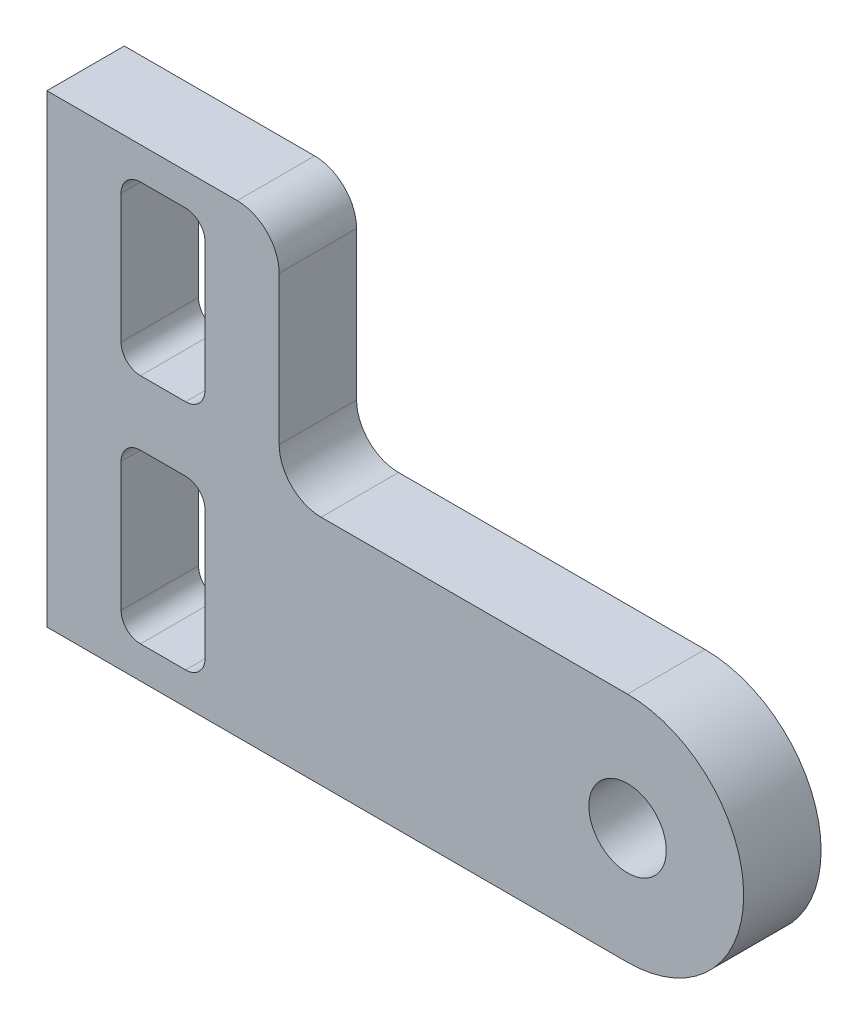
SolidWorks part; units mm, degrees
ref_plane "Alzado" through (0, 0, 0) normal (0, 0, 1) x (1, 0, 0)
ref_plane "Planta" through (0, 0, 0) normal (0, 1, 0) x (1, 0, 0)
ref_plane "Vista lateral" through (0, 0, 0) normal (1, 0, 0) x (0, 0, -1)
sketch "Model" plane through (0, 0, 0) normal (0, 0, 1) x (1, 0, 0)
  line L0 (182.2229, 265.8965) -> (183.9729, 265.8965)
  line L1 (184.7229, 266.6465) -> (184.7229, 271.6465)
  line L2 (183.9729, 272.3965) -> (182.2229, 272.3965)
  line L3 (181.4729, 271.6465) -> (181.4729, 266.6465)
  line L4 (185.9729, 282.6465) -> (178.5979, 282.6465)
  line L5 (182.2229, 274.896) -> (183.9729, 274.896)
  line L6 (184.7229, 275.646) -> (184.7229, 280.646)
  line L7 (183.9729, 281.396) -> (182.2229, 281.396)
  line L8 (181.4729, 280.646) -> (181.4729, 275.646)
  line L9 (178.5979, 282.6465) -> (178.5979, 264.6465)
  line L10 (187.5979, 281.0215) -> (187.5979, 275.2715)
  line L11 (189.2229, 273.6465) -> (201.0979, 273.6465)
  line L12 (201.0979, 264.6465) -> (178.5979, 264.6465)
  circle A0 centre (201.0979, 269.1465) radius 1.5
  arc A1 (181.4729, 266.6465) -> (182.2229, 265.8965) centre (182.2229, 266.6465) ccw
  arc A2 (183.9729, 265.8965) -> (184.7229, 266.6465) centre (183.9729, 266.6465) ccw
  arc A3 (184.7229, 271.6465) -> (183.9729, 272.3965) centre (183.9729, 271.6465) ccw
  arc A4 (182.2229, 272.3965) -> (181.4729, 271.6465) centre (182.2229, 271.6465) ccw
  arc A5 (181.4729, 275.646) -> (182.2229, 274.896) centre (182.2229, 275.646) ccw
  arc A6 (183.9729, 274.896) -> (184.7229, 275.646) centre (183.9729, 275.646) ccw
  arc A7 (184.7229, 280.646) -> (183.9729, 281.396) centre (183.9729, 280.646) ccw
  arc A8 (182.2229, 281.396) -> (181.4729, 280.646) centre (182.2229, 280.646) ccw
  arc A9 (201.0979, 264.6465) -> (201.0979, 273.6465) centre (201.0979, 269.1465) ccw
  arc A10 (187.5979, 275.2715) -> (189.2229, 273.6465) centre (189.2229, 275.2715) ccw
  arc A11 (187.5979, 281.0215) -> (185.9729, 282.6465) centre (185.9729, 281.0215) ccw
extrude "Saliente-Extruir1" add sketch "Model" along normal blind 3
